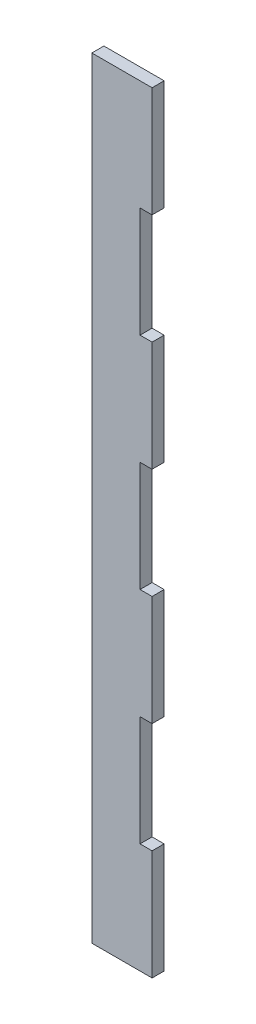
SolidWorks part; units mm, degrees
ref_plane "Front Plane" through (0, 0, 0) normal (0, 0, 1) x (1, 0, 0)
ref_plane "Top Plane" through (0, 0, 0) normal (0, 1, 0) x (1, 0, 0)
ref_plane "Right Plane" through (0, 0, 0) normal (1, 0, 0) x (0, 0, -1)
sketch "Sketch1" plane through (0, 0, 0) normal (0, 0, 1) x (1, 0, 0)
  line L0 (0, 101.6) -> (0, -101.6) construction
  line L1 (-6.35, 101.6) -> (6.35, 101.6)
  line L2 (-6.35, 101.6) -> (-6.35, -101.6)
  line L3 (-6.35, -101.6) -> (6.35, -101.6)
  line L4 (6.35, 101.6) -> (6.35, -101.6)
  line L5 (6.35, 72.5714) -> (6.35, 43.5429)
  line L6 (6.35, 101.6) -> (9.525, 101.6)
  line L7 (6.35, 101.6) -> (6.35, 72.5714)
  line L8 (6.35, 72.5714) -> (9.525, 72.5714)
  line L9 (9.525, 101.6) -> (9.525, 72.5714)
  line L10 (6.35, 72.5714) -> (9.525, 72.5714)
  line L11 (9.525, 72.5714) -> (9.525, 43.5429)
  line L12 (6.35, 43.5429) -> (9.525, 43.5429)
  line L13 (6.35, 43.5429) -> (6.35, 14.5143)
  line L14 (6.35, 43.5429) -> (9.525, 43.5429)
  line L15 (9.525, 43.5429) -> (9.525, 14.5143)
  line L16 (6.35, 14.5143) -> (9.525, 14.5143)
  line L17 (6.35, 14.5143) -> (6.35, -14.5143)
  line L18 (6.35, 14.5143) -> (9.525, 14.5143)
  line L19 (9.525, 14.5143) -> (9.525, -14.5143)
  line L20 (6.35, -14.5143) -> (9.525, -14.5143)
  line L21 (6.35, -14.5143) -> (6.35, -43.5429)
  line L22 (6.35, -14.5143) -> (9.525, -14.5143)
  line L23 (9.525, -14.5143) -> (9.525, -43.5429)
  line L24 (6.35, -43.5429) -> (9.525, -43.5429)
  line L25 (6.35, -43.5429) -> (6.35, -72.5714)
  line L26 (6.35, -43.5429) -> (9.525, -43.5429)
  line L27 (9.525, -43.5429) -> (9.525, -72.5714)
  line L28 (6.35, -72.5714) -> (9.525, -72.5714)
  line L29 (6.35, -72.5714) -> (6.35, -101.6)
  line L30 (6.35, -72.5714) -> (9.525, -72.5714)
  line L31 (9.525, -72.5714) -> (9.525, -101.6)
  line L32 (6.35, -101.6) -> (9.525, -101.6)
  point P6 (0, 0)
  dimension "D2" = 12.7
  dimension "D1" = 203.2
  dimension "D3" = 29.0286
  dimension "D4" = 3.175
  dimension "D5" = 7
extrude "Boss-Extrude1" add sketch "Sketch1" along normal blind 3.175 contours L0 L1 L2 L3 | L1 L0 L3 L4 | L9 L6 L4 L8 | L4 L16 L15 L12 | L4 L24 L23 L20 | L4 L32 L31 L28
equation "\"Height\"= 12in"
equation "\"Depth\"= 7in"
equation "\"WallThickness\"= 0.125in"
equation "\"FloorThickness\"= 0.25in"
equation "\"Width\" = 30in"
equation "\"D1@Boss-Extrude1\"=\"WallThickness\""
equation "\"D3@Sketch1\"=\"D1@Sketch1\"/\"D5@Sketch1\""
equation "\"D4@Sketch1\"=\"WallThickness\""
